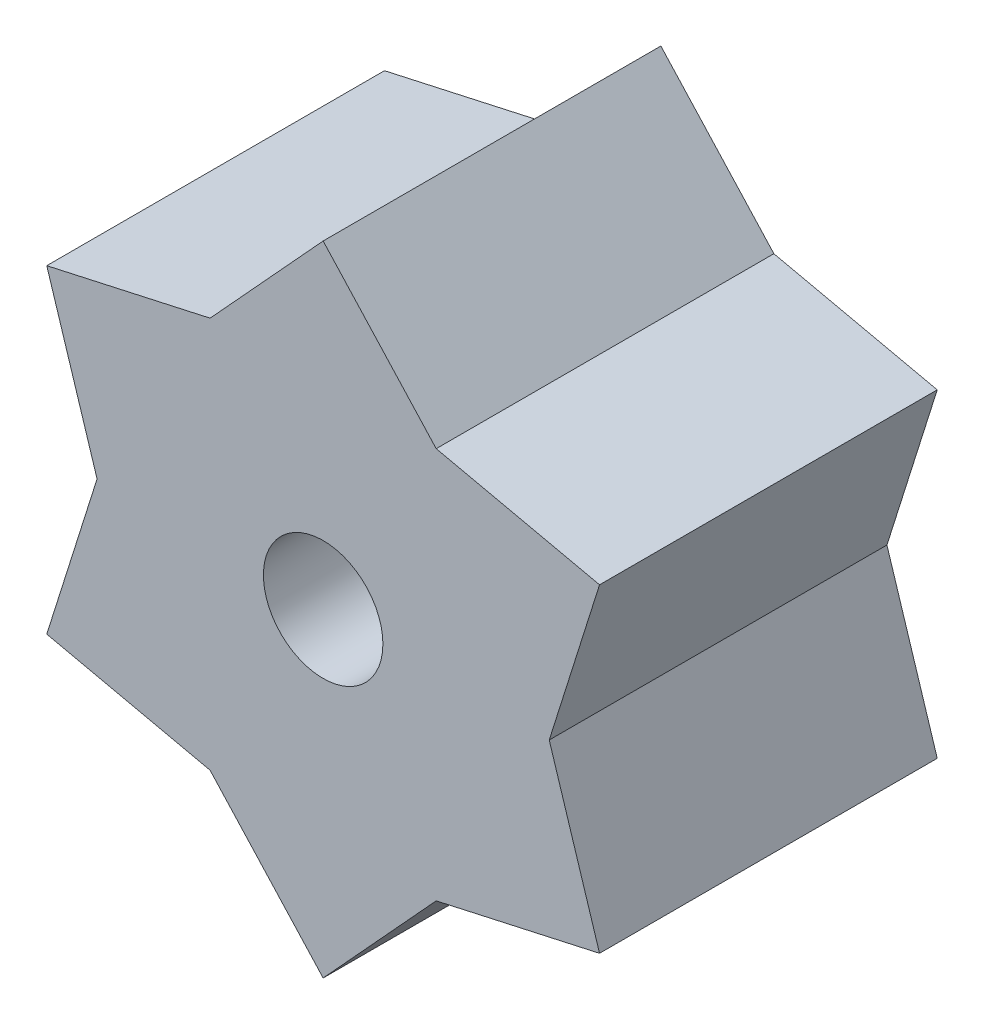
SolidWorks part; units mm, degrees
ref_plane "Front Plane" through (0, 0, 0) normal (0, 0, 1) x (1, 0, 0)
ref_plane "Top Plane" through (0, 0, 0) normal (0, 1, 0) x (1, 0, 0)
ref_plane "Right Plane" through (0, 0, 0) normal (1, 0, 0) x (0, 0, -1)
sketch "Sketch1" plane through (0, 0, 0) normal (0, 0, 1) x (1, 0, 0)
  line L0 (0, 6.1428) -> (0, -5.749) construction
  line L1 (-3.0597, 2.8037) -> (0, 6.1428)
  line L2 (0, 6.1428) -> (3.0597, 2.8037)
  line L3 (0.8982, 4.0516) -> (5.3198, 3.0714)
  line L4 (5.3198, 3.0714) -> (3.9579, -1.2479)
  line L5 (3.9579, 1.2479) -> (5.3198, -3.0714)
  line L6 (5.3198, -3.0714) -> (0.8982, -4.0516)
  line L7 (3.0597, -2.8037) -> (0, -6.1428)
  line L8 (0, -6.1428) -> (-3.0597, -2.8037)
  line L9 (-0.8982, -4.0516) -> (-5.3198, -3.0714)
  line L10 (-5.3198, -3.0714) -> (-3.9579, 1.2479)
  line L11 (-3.9579, -1.2479) -> (-5.3198, 3.0714)
  line L12 (-5.3198, 3.0714) -> (-0.8982, 4.0516)
  circle A0 centre (0, 0) radius 1.15
  circle A1 centre (0, 0) radius 4.15
  point P26 (0, 0)
  dimension "D1" = 2.3
  dimension "D3" = 85
  dimension "D4" = 42.5
  dimension "D2" = 3
  dimension "D5" = 6
extrude "Boss-Extrude1" add sketch "Sketch1" against normal blind 6.5
